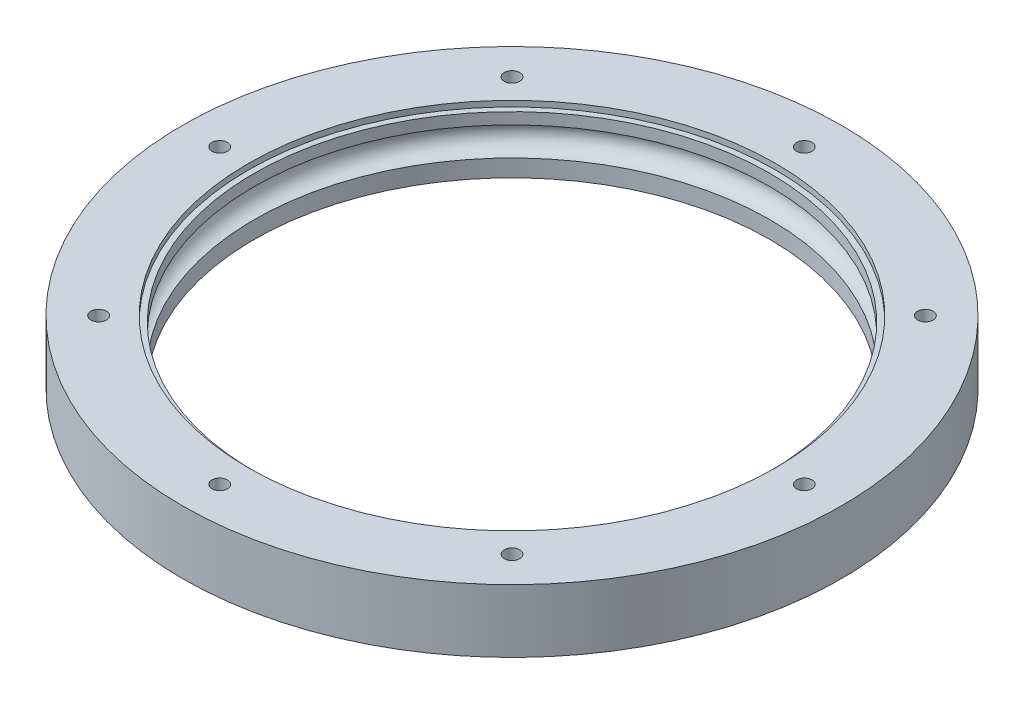
SolidWorks part; units mm, degrees
ref_plane "Front Plane" through (0, 0, 0) normal (0, 0, 1) x (1, 0, 0)
ref_plane "Top Plane" through (0, 0, 0) normal (0, 1, 0) x (1, 0, 0)
ref_plane "Right Plane" through (0, 0, 0) normal (1, 0, 0) x (0, 0, -1)
sketch "Sketch2" plane through (0, 0, 0) normal (0, 0, 1) x (1, 0, 0)
  line L0 (0, 0) -> (-45, 0) construction
  line L1 (-45, 0) -> (-45, 11) construction
  line L2 (-45, 10) -> (-57.5, 10)
  line L3 (-57.5, 10) -> (-57.5, 11)
  line L4 (-45, 10) -> (-45, 0)
  line L5 (-57.5, 11) -> (-46, 11)
  line L6 (-57.5, 10) -> (-57.5, 0)
  line L7 (-57.5, 0) -> (-45, 0)
  line L8 (-46, 10) -> (-46, 11)
  line L9 (0, 0) -> (0, 46.7003) construction
  arc A0 (-45, 8) -> (-45, 3) centre (-45, 5.5) ccw
  dimension "D4" = 2.5
  dimension "D1" = 45
  dimension "D2" = 11
  dimension "D3" = 3
  dimension "D5" = 2
  dimension "D6" = 12.5
  dimension "D7" = 2
revolve "Revolve1" add sketch "Sketch2" angle 360 about L9
ref_plane "ball center plane" through (0, 5.5, 0) normal (0, 1, 0) x (1, 0, 0)
sketch "Sketch3" plane through (0, 11, 0) normal (0, 1, 0) x (1, 0, 0)
  circle A1 centre (-36.0624, -36.0624) radius 1.35
  circle A2 centre (-36.0624, -36.0624) radius 1.35
  circle A3 centre (0, -51) radius 1.35
  circle A4 centre (0, -51) radius 1.35
  circle A5 centre (36.0624, -36.0624) radius 1.35
  circle A6 centre (36.0624, -36.0624) radius 1.35
  circle A7 centre (51, 0) radius 1.35
  circle A8 centre (51, 0) radius 1.35
  circle A9 centre (36.0624, 36.0624) radius 1.35
  circle A10 centre (36.0624, 36.0624) radius 1.35
  circle A11 centre (0, 51) radius 1.35
  circle A12 centre (0, 51) radius 1.35
  circle A13 centre (-36.0624, 36.0624) radius 1.35
  circle A14 centre (-36.0624, 36.0624) radius 1.35
  circle A15 centre (-51, 0) radius 1.35
  circle A16 centre (-51, 0) radius 1.35
  dimension "D1" = 0
  dimension "D2" = 0
  dimension "D3" = 0
  dimension "D4" = 0
  dimension "D5" = 0
  dimension "D6" = 0
  dimension "D7" = 0
  dimension "D8" = 0
extrude "Cut-Extrude1" cut sketch "Sketch3" against normal through all
